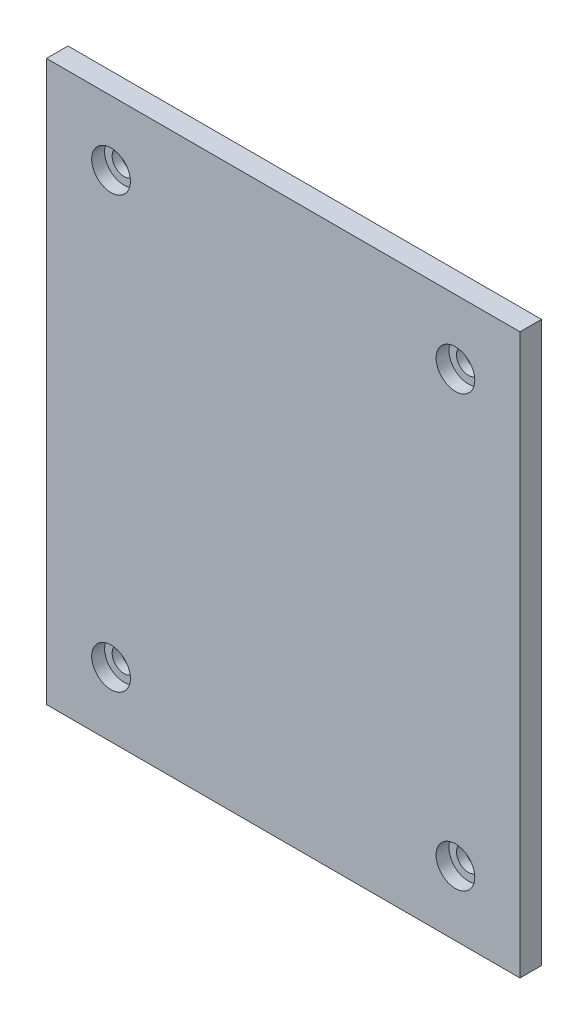
SolidWorks part; units mm, degrees
material "6061 Alloy"
ref_plane "Front Plane" through (0, 0, 0) normal (1, 0, 0) x (0, 1, 0)
ref_plane "Top Plane" through (0, 0, 0) normal (0, 0, 1) x (0, 1, 0)
ref_plane "Right Plane" through (0, 0, 0) normal (0, 1, 0) x (-1, 0, 0)
sketch "Sketch1" plane through (0, 0, 0) normal (0, 0, 1) x (0, 1, 0)
  line L1 (65, 55) -> (-65, 55)
  line L2 (65, 55) -> (65, -55)
  line L3 (65, -55) -> (-65, -55)
  line L4 (-65, 55) -> (-65, -55)
  line L5 (65, 55) -> (-65, -55) construction
  line L6 (65, -55) -> (-65, 55) construction
  point P0 (0, 0)
  dimension "D1" = 130
  dimension "D2" = 110
extrude "Boss-Extrude1" add sketch "Sketch1" along normal blind 5
sketch "Sketch3" plane through (0, 0, 5) normal (0, 0, 1) x (1, 0, 0)
  line L0 (-55, 65) -> (-55, -65) construction
  line L1 (55, 65) -> (-55, 65) construction
  circle A0 centre (-40, 50) radius 2.75
  circle A1 centre (40, -50) radius 2.75
  circle A2 centre (-40, -50) radius 2.75
  circle A3 centre (40, 50) radius 2.75
  point P6 (24.824, -30.9859)
  point P9 (-22.1831, -34.331)
  dimension "D1" = 5.5
  dimension "D2" = 15
  dimension "D3" = 95
  dimension "D4" = 15
  dimension "D5" = 95
  dimension "D6" = 115
  dimension "D7" = 15
  dimension "D8" = 115
  dimension "D9" = 15
extrude "Cut-Extrude1" cut sketch "Sketch3" against normal through all
sketch "Sketch4" plane through (0, 0, 5) normal (0, 0, 1) x (1, 0, 0)
  circle A0 centre (-40, 50) radius 4.5
  circle A1 centre (40, 50) radius 4.5
  circle A2 centre (40, -50) radius 4.5
  circle A3 centre (-40, -50) radius 4.5
  dimension "D1" = 9
  dimension "D2" = 9
  dimension "D3" = 9
  dimension "D4" = 9
extrude "Cut-Extrude2" cut sketch "Sketch4" against normal blind 3
